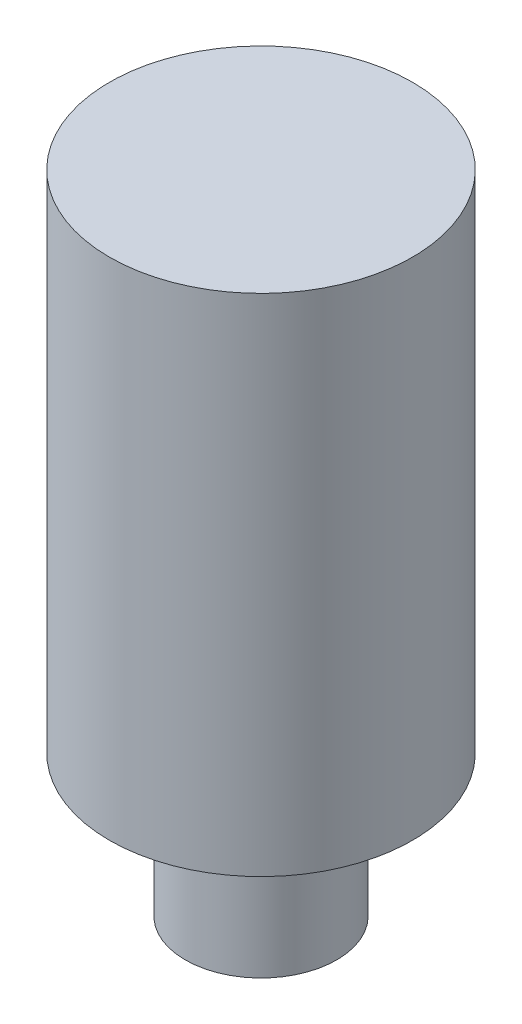
SolidWorks part; units mm, degrees
ref_plane "前基準面" through (0, 0, 0) normal (0, 0, 1) x (1, 0, 0)
ref_plane "上基準面" through (0, 0, 0) normal (0, 1, 0) x (1, 0, 0)
ref_plane "右基準面" through (0, 0, 0) normal (1, 0, 0) x (0, 0, -1)
sketch "草圖1" plane through (0, 0, 0) normal (0, 1, 0) x (1, 0, 0)
  circle A0 centre (0, 0) radius 1.5
extrude "填料-伸長1" add sketch "草圖1" along normal blind 2.8
sketch "草圖2" plane through (0, 2.8, 0) normal (0, 1, 0) x (1, 0, 0)
  circle A0 centre (0, 0) radius 3
extrude "填料-伸長2" add sketch "草圖2" along normal blind 10
